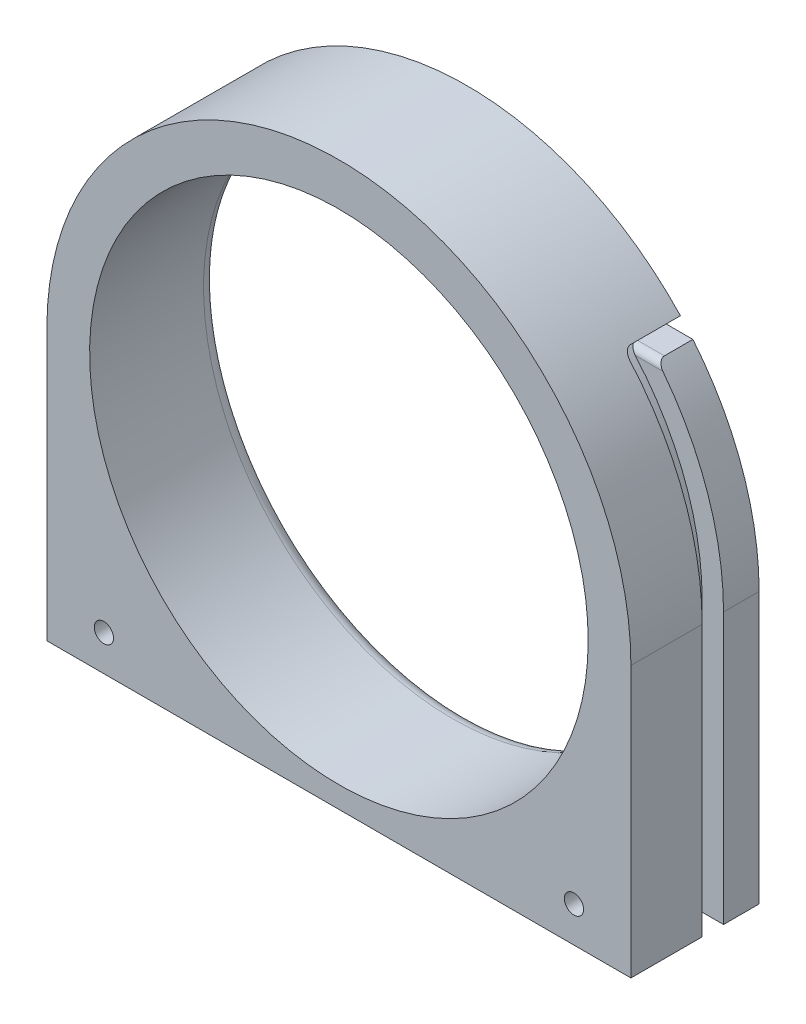
SolidWorks part; units mm, degrees
material "ABS"
ref_plane "前视基准面" through (0, 0, 0) normal (0, 0, 1) x (1, 0, 0)
ref_plane "上视基准面" through (0, 0, 0) normal (0, 1, 0) x (1, 0, 0)
ref_plane "右视基准面" through (0, 0, 0) normal (1, 0, 0) x (0, 0, -1)
sketch "草图1" plane through (0, 0, 0) normal (0, 0, 1) x (1, 0, 0)
  line L0 (-41, 0) -> (-41, -38)
  line L1 (41, 0) -> (41, -38)
  line L2 (-41, -38) -> (41, -38)
  arc A0 (41, 0) -> (-41, 0) centre (0, 0) ccw
  circle A1 centre (0, 0) radius 35
  dimension "D1" = 70
  dimension "D2" = 82
  dimension "D3" = 38
  dimension "D4" = 38
extrude "厚度21" add sketch "草图1" along normal blind 20
sketch "草图5" plane through (0, 0, 0) normal (0, 0, -1) x (-1, 0, 0)
  line L0 (0, 35) -> (0, 28) construction
  line L1 (-25.6905, 28) -> (-21, 28)
  line L2 (-27.7128, 26) -> (-23.4307, 26)
  line L3 (27.7128, 26) -> (23.4307, 26)
  line L4 (21, 28) -> (25.6905, 28)
  arc A1 (-21, 28) -> (-23.4307, 26) centre (0, 0) ccw
  arc A3 (-25.6905, 28) -> (-27.7128, 26) centre (0, 0) ccw
  arc A4 (23.4307, 26) -> (0, 35) centre (0, 0) ccw
  arc A5 (27.7128, 26) -> (25.6905, 28) centre (0, 0) ccw
  circle M5 centre (0, 0) radius 35
  dimension "D2" = 76
  dimension "D1" = 7
extrude "切除-拉伸2" cut sketch "草图5" against normal blind 4 contours L1 A3 L2 M5 | L3 A5 L4 M5
sketch "草图6" plane through (0, 0, 0) normal (0, 0, -1) x (-1, 0, 0)
  line L0 (-25.6905, 28) -> (-37.167, 28)
  line L1 (-37.167, 28) -> (-37.167, 26)
  line L2 (-37.167, 26) -> (-27.7128, 26)
  line L3 (0, 0) -> (0, 14.6011)
  line L6 (37.167, 26) -> (27.7128, 26)
  line L7 (37.167, 28) -> (37.167, 26)
  line L8 (25.6905, 28) -> (37.167, 28)
  arc A0 (27.7128, 26) -> (25.6905, 28) centre (0, 0) ccw
  arc A2 (-25.6905, 28) -> (-27.7128, 26) centre (0, 0) ccw
  arc M1 (41, 0) -> (-41, 0) centre (0, 0) ccw
  arc M8 (-27.7128, 26) -> (-25.6905, 28) centre (0, 0) cw
  arc M12 (25.6905, 28) -> (27.7128, 26) centre (0, 0) cw
  dimension "D1" = 2
extrude "切除-拉伸3" cut sketch "草图6" against normal blind 8 contours L2 L0 M1 M8 | L8 L6 M12 M1 | L8 L6 L7 M1 | L1 L2 L0 M1
sketch "草图7" plane through (0, 0, 8) normal (0, 0, -1) x (-1, 0, 0)
  line L0 (-38, -36) -> (38, -36)
  line L1 (0, 0) -> (0, 19.2803)
  line L2 (41, -38) -> (-41, -38)
  line L3 (-29.95, 28) -> (-25.6905, 28)
  line L5 (-41, 0) -> (-41, -38)
  line L6 (25.6905, 28) -> (29.95, 28)
  line L9 (41, -38) -> (-41, -38) construction
  line L10 (-38, -36) -> (-38, 0)
  line L11 (38, 0) -> (38, -36)
  line L13 (41, -38) -> (41, 0)
  arc A0 (38, 0) -> (25.6905, 28) centre (0, 0) ccw
  arc A1 (41, 0) -> (29.95, 28) centre (0, 0) ccw
  arc A2 (-25.6905, 28) -> (-38, 0) centre (0, 0) ccw
  arc A3 (-29.95, 28) -> (-41, 0) centre (0, 0) ccw
  dimension "D1" = 2
extrude "切除-拉伸4" cut sketch "草图7" against normal blind 2 and the other way blind 1 contours L11 L0 L10 A2 L3 A3 L5 L2 L13 A1 L6 A0
fillet "圆角1" radius 1 8 edges at (-27.8202, 28, 10) (-26.7204, 27.0189, 4) (-29.7073, 26, 7) (-38, -36, 8.5) (38, -36, 8.5) (27.8202, 28, 10) (29.7073, 26, 7) (26.7204, 27.0189, 4)
sketch "草图8" plane through (0, -38, 0) normal (0, -1, 0) x (1, 0, 0)
  line L0 (-41, 0) -> (-41, 2)
  line L1 (-41, 7) -> (-41, 0) construction
  line L2 (-41, 2) -> (41, 2)
  line L3 (41, 7) -> (41, 0) construction
  line L4 (41, 2) -> (41, 0)
  line L5 (41, 0) -> (-41, 0)
  dimension "D1" = 2
extrude "切除-拉伸5" cut sketch "草图8" against normal through all
fillet "圆角3" radius 2 2 edges at (0, -35, 2) (0, 35, 2)
sketch "草图9" plane through (0, -38, 0) normal (0, -1, 0) x (1, 0, 0)
  line L0 (-41, 20) -> (-41, 10) construction
  line L1 (-41, 20) -> (41, 20) construction
  line L2 (0, 0) -> (0, 12.1634)
  circle A0 centre (-26, 15) radius 1.25
  circle A1 centre (26, 15) radius 1.25
  dimension "D1" = 2.5
  dimension "D2" = 15
  dimension "D3" = 5
sketch "草图10" plane through (0, 0, 20) normal (0, 0, 1) x (1, 0, 0)
  line L0 (0, 0) -> (0, 4.6689) construction
  circle A0 centre (-33, -33) radius 1.2815
  circle A1 centre (33, -33) radius 1.2815
  dimension "D1" = 33
  dimension "D2" = 33
hole_wizard "Ø2.7 (2.7) 直径孔1" positions "3D草图2" profile "草图12" hole size "Ø2.7" standard "GB"
sketch3d "3D草图2"
  point P0 (-33, -33, 20)
  point P3 (33, -33, 20)
  point P6 (26, -38, 15)
  point P9 (-26, -38, 15)
sketch "草图12" plane through (-33, -33, 20) normal (1, 0, 0) x (0, -1, 0)
  line L0 (0, 0) -> (0, 7.8112)
  line L1 (0, 7.8112) -> (1.35, 7)
  line L2 (1.35, 7) -> (1.35, 0)
  line L5 (1.35, 0) -> (0, 0)
  line L10 (0, 7.8112) -> (-1.35, 7) construction
  line L11 (0, -6.35) -> (0, 107.95) construction
  dimension "孔直径" = 2.7
  dimension "孔深度" = 7
  dimension "导头角度" = 118
